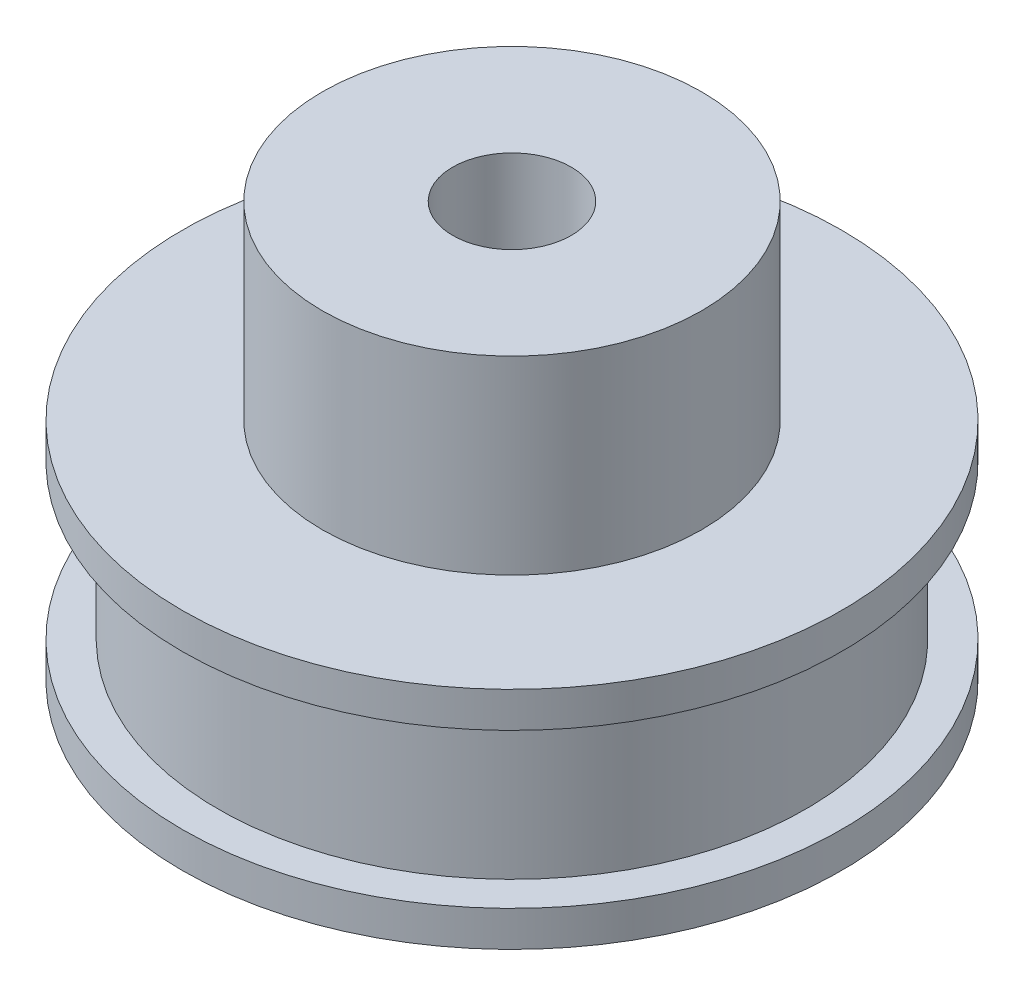
SolidWorks part; units mm, degrees
ref_plane "Face" through (0, 0, 0) normal (0, 0, 1) x (1, 0, 0)
ref_plane "Dessus" through (0, 0, 0) normal (0, 1, 0) x (1, 0, 0)
ref_plane "Droite" through (0, 0, 0) normal (1, 0, 0) x (0, 0, -1)
sketch "Esquisse1" plane through (0, 0, 0) normal (0, 0, 1) x (1, 0, 0)
  line L0 (0, 0) -> (0, 9.7978) construction
  line L1 (2.5, 0) -> (13.9, 0)
  line L2 (13.9, 0) -> (13.9, 1.5)
  line L3 (13.9, 1.5) -> (12.4, 1.5)
  line L4 (12.4, 1.5) -> (12.4, 8)
  line L5 (12.4, 8) -> (13.9, 8)
  line L6 (13.9, 8) -> (13.9, 9.5)
  line L7 (13.9, 9.5) -> (8.85, 9.5)
  line L8 (8.85, 9.5) -> (8.85, 17.5)
  line L9 (8.85, 17.5) -> (2.5, 17.5)
  line L10 (2.5, 17.5) -> (2.5, 0)
  dimension "D1" = 27.8
  dimension "D2" = 6.5
  dimension "D3" = 5
  dimension "D4" = 17.7
  dimension "D5" = 17.5
  dimension "D6" = 1.5
  dimension "D7" = 1.5
  dimension "D8" = 1.5
revolve "Révolution1" add sketch "Esquisse1" angle 360 about L0
sketch "Esquisse2" plane through (0, 17.5, 0) normal (0, 1, 0) x (1, 0, 0)
  circle A0 centre (0, 0) radius 8
  circle A1 centre (0, 0) radius 8.85
  dimension "D1" = 16
extrude "Enlèv. mat.-Extru.1" cut sketch "Esquisse2" against normal blind 8
